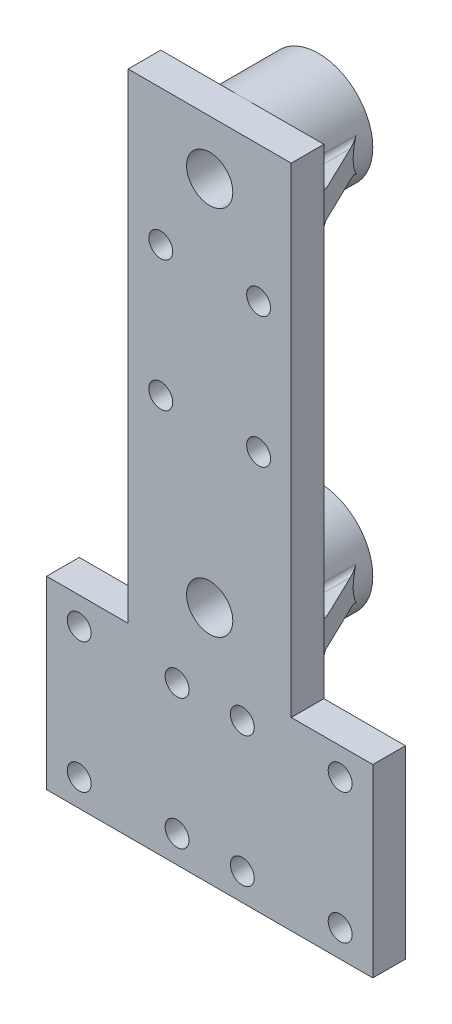
SolidWorks part; units mm, degrees
ref_plane "Front Plane" through (0, 0, 0) normal (0, 0, 1) x (1, 0, 0)
ref_plane "Top Plane" through (0, 0, 0) normal (0, 1, 0) x (1, 0, 0)
ref_plane "Right Plane" through (0, 0, 0) normal (1, 0, 0) x (0, 0, -1)
sketch "Sketch1" plane through (0, 0, 0) normal (0, 0, 1) x (1, 0, 0)
  line L1 (-15, 51.15) -> (15, 51.15)
  line L2 (-15, 51.15) -> (-15, -17.15)
  line L3 (-15, -51.15) -> (15, -51.15)
  line L4 (15, 51.15) -> (15, -17.15)
  line L5 (-15, 51.15) -> (15, -51.15) construction
  line L6 (-15, -51.15) -> (15, 51.15) construction
  line L11 (-15, 17.15) -> (15, 51.15) construction
  line L12 (-15, 51.15) -> (15, 17.15) construction
  line L23 (-9, 46.15) -> (9, 22.15) construction
  line L24 (-9, 22.15) -> (9, 46.15) construction
  line L25 (-15, -17.15) -> (-30, -17.15)
  line L26 (-30, -17.15) -> (-30, -51.15)
  line L27 (-30, -51.15) -> (-15, -51.15)
  line L28 (15, -17.15) -> (30, -17.15)
  line L29 (30, -17.15) -> (30, -51.15)
  line L30 (30, -51.15) -> (15, -51.15)
  line L42 (-30, -51.15) -> (0, -17.15) construction
  line L43 (-30, -17.15) -> (0, -51.15) construction
  line L48 (0, -17.15) -> (30, -51.15) construction
  line L49 (0, -51.15) -> (30, -17.15) construction
  line L54 (-24, -22.15) -> (-6, -46.15) construction
  line L55 (-24, -46.15) -> (-6, -22.15) construction
  line L60 (6, -22.15) -> (24, -46.15) construction
  line L61 (6, -46.15) -> (24, -22.15) construction
  circle A0 centre (9, 46.15) radius 2.2
  circle A1 centre (-9, 46.15) radius 2.2
  circle A2 centre (-9, 22.15) radius 2.2
  circle A3 centre (9, 22.15) radius 2.2
  circle A4 centre (-6, -22.15) radius 2.2
  circle A6 centre (-24, -22.15) radius 2.2
  circle A7 centre (-24, -46.15) radius 2.2
  circle A8 centre (-6, -46.15) radius 2.2
  circle A9 centre (6, -22.15) radius 2.2
  circle A10 centre (24, -22.15) radius 2.2
  circle A11 centre (6, -46.15) radius 2.2
  circle A12 centre (24, -46.15) radius 2.2
  point P0 (0, 0)
  point P6 (0, 34.15)
  point P11 (0, -34.15)
  point P14 (0, 34.15)
  point P17 (-15, -34.15)
  point P18 (15, -34.15)
  point P19 (-15, -34.15)
  point P35 (15, -34.15)
  dimension "D9" = 15
  dimension "D16" = 4.4
  dimension "D1" = 102.3
  dimension "D2" = 30
  dimension "D3" = 34
  dimension "D4" = 34
  dimension "D5" = 30
  dimension "D6" = 30
  dimension "D7" = 24
  dimension "D8" = 18
  dimension "D10" = 15
  dimension "D11" = 30
  dimension "D12" = 24
  dimension "D13" = 18
  dimension "D14" = 24
  dimension "D15" = 18
extrude "Boss-Extrude1" add sketch "Sketch1" along normal blind 6
sketch "Sketch4" plane through (0, 51.15, 0) normal (0, 1, 0) x (1, 0, 0)
  line L1 (-15, 0) -> (15, 0)
  line L2 (-15, 0) -> (-15, -6)
  line L3 (-15, -6) -> (15, -6)
  line L4 (15, 0) -> (15, -6)
extrude "Boss-Extrude3" add sketch "Sketch4" along normal blind 20
sketch "Sketch5" plane through (0, 0, 6) normal (0, 0, 1) x (1, 0, 0)
  line L5 (-15, 51.15) -> (15, 71.15) construction
  line L6 (-15, 71.15) -> (15, 51.15) construction
  circle A0 centre (0, 61.15) radius 10
  circle A1 centre (0, 61.15) radius 4.25
  point P0 (0, 61.15)
  dimension "D1" = 20
extrude "Boss-Extrude4" add sketch "Sketch5" against normal blind 20
sketch "Sketch7" plane through (0, 0, 0) normal (0, 0, -1) x (-1, 0, 0)
  circle A0 centre (0, 61.15) radius 4.25
extrude "Cut-Extrude1" cut sketch "Sketch7" against normal blind 20
ref_plane "Plane1" through (0, 61, 0) normal (0, 1, 0) x (1, 0, 0)
sketch "Sketch8" plane through (0, 61, 0) normal (0, 1, 0) x (1, 0, 0)
  line L0 (15, 0) -> (10, 10.3935)
  line L1 (10, 0) -> (10, 14) construction
rib "Rib1" sketch "Sketch8" sketch "Sketch8" thickness 5 extrusion direction parallel to sketch draft on no parameters "D1"=5
pattern_circular "CirPattern2" count 2 over 180 about axis through (0, 61.15, -14) along (0, 0, 1) of "Rib1"
pattern_linear "LPattern3" count 2 spacing 68.3 along (0, -1, 0) of "CirPattern2", "Boss-Extrude4", "Rib1"
fillet "Fillet4" radius 1 16 edges at (12.36, 63.5, 0) (9.72, 63.5, -5.4878) (9.6425, 58.5, -5.5683) (12.3212, 58.5, 0) (-9.6425, 63.8, -5.5683) (-12.3212, 63.8, 0) (-12.36, 58.8, 0) (-9.72, 58.8, -5.4878) (12.36, -4.8, 0) (9.6425, -9.8, -5.5683) (9.72, -4.8, -5.4878) (12.3212, -9.8, 0) (-9.6425, -4.5, -5.5683) (-12.36, -9.5, 0) (-9.72, -9.5, -5.4878) (-12.3212, -4.5, 0)
sketch "Sketch9" plane through (0, 0, 0) normal (0, 0, -1) x (-1, 0, 0)
  circle A0 centre (0, -7.15) radius 4.25
extrude "Cut-Extrude2" cut sketch "Sketch9" against normal blind 20
